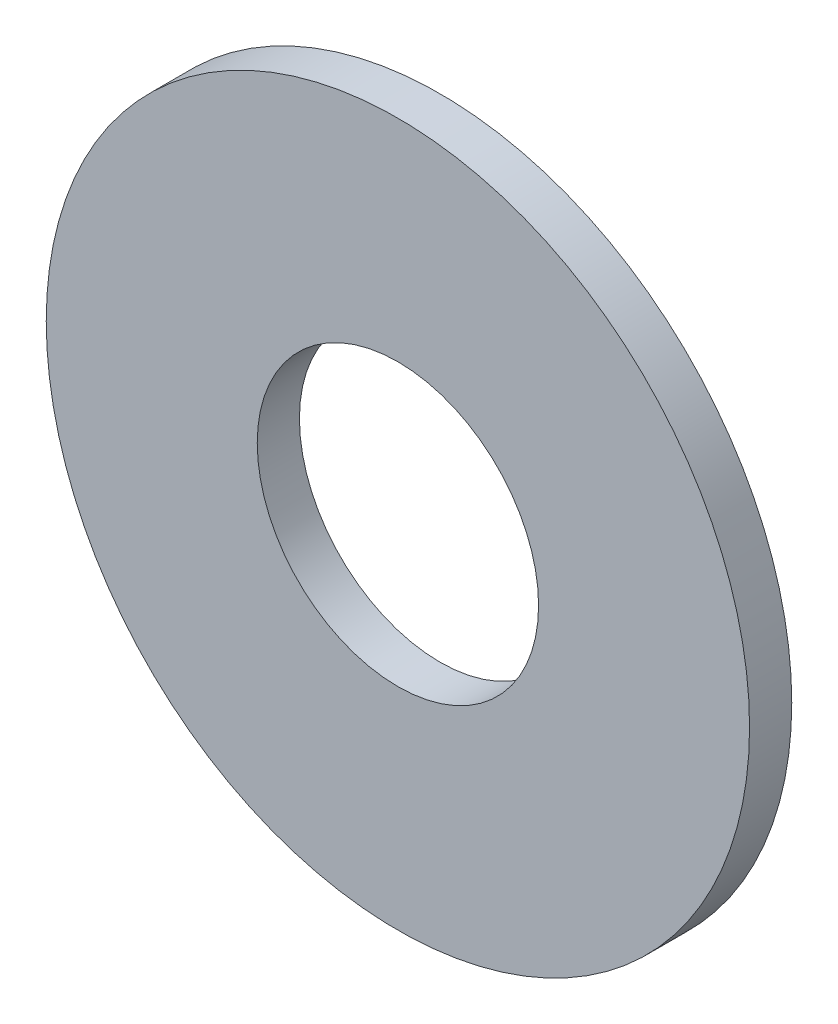
SolidWorks part; units mm, degrees
material "Stainless Steel (ferritic)"
ref_plane "Front Plane" through (0, 0, 0) normal (0, 0, 1) x (1, 0, 0)
ref_plane "Top Plane" through (0, 0, 0) normal (0, 1, 0) x (1, 0, 0)
ref_plane "Right Plane" through (0, 0, 0) normal (1, 0, 0) x (0, 0, -1)
sketch "Sketch1" plane through (0, 0, 0) normal (0, 0, 1) x (1, 0, 0)
  circle A0 centre (0, 0) radius 1
  circle A1 centre (0, 0) radius 2.5
  dimension "D1" = 2
  dimension "D2" = 5
extrude "Boss-Extrude1" add sketch "Sketch1" against normal blind 0.3
